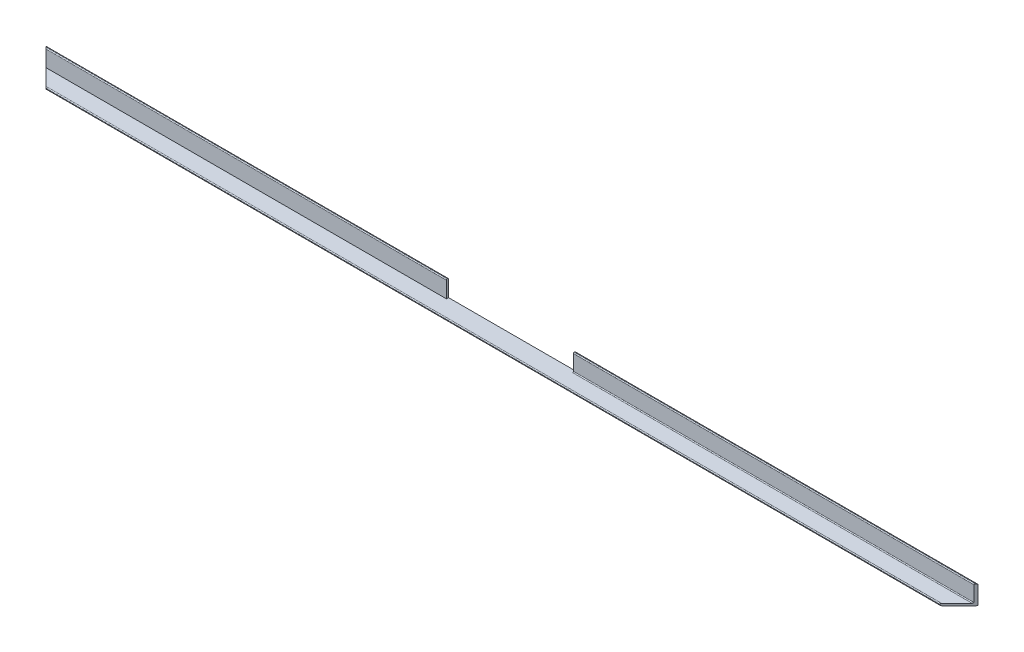
SolidWorks part; units mm, degrees
ref_plane "Front Plane" through (0, 0, 0) normal (0, 0, 1) x (1, 0, 0)
ref_plane "Top Plane" through (0, 0, 0) normal (0, 1, 0) x (1, 0, 0)
ref_plane "Right Plane" through (0, 0, 0) normal (1, 0, 0) x (0, 0, -1)
sketch "Sketch1" plane through (0, 0, 0) normal (0, 1, 0) x (1, 0, 0)
  line L1 (-550, 11.25) -> (550, 11.25)
  line L2 (-550, 11.25) -> (-550, -11.25)
  line L3 (-550, -11.25) -> (550, -11.25)
  line L4 (550, 11.25) -> (550, -11.25)
  line L5 (-550, 11.25) -> (550, -11.25) construction
  line L6 (-550, -11.25) -> (550, 11.25) construction
  point P0 (0, 0)
  dimension "D1" = 1100
  dimension "D2" = 22.5
extrude "Boss-Extrude1" add sketch "Sketch1" along normal blind 2.5
sketch "Sketch2" plane through (0, 2.5, 0) normal (0, 1, 0) x (1, 0, 0)
  line L0 (550, -11.25) -> (550, 11.25) construction
  line L1 (-550, 11.25) -> (550, 11.25)
  line L2 (-550, 11.25) -> (-550, 8.75)
  line L3 (-550, 8.75) -> (550, 8.75)
  line L4 (550, 11.25) -> (550, 8.75)
  dimension "D1" = 2.5
extrude "Boss-Extrude2" add sketch "Sketch2" along normal blind 20
sketch "Sketch3" plane through (0, 0, -8.75) normal (0, 0, 1) x (1, 0, 0)
  line L0 (-550, 22.5) -> (550, 22.5) construction
  line L1 (-75, 22.5) -> (75, 22.5)
  line L2 (-75, 22.5) -> (-75, 2.5)
  line L3 (-75, 2.5) -> (75, 2.5)
  line L4 (75, 22.5) -> (75, 2.5)
  line L5 (-550, 2.5) -> (550, 2.5) construction
  line L6 (-550, 22.5) -> (-550, 2.5) construction
  line L7 (550, 22.5) -> (550, 2.5) construction
  point P10 (-550, 12.5)
  point P13 (550, 12.5)
  dimension "D1" = 150
  dimension "D2" = 475
  dimension "D3" = 475
extrude "Cut-Extrude1" cut sketch "Sketch3" against normal blind 10
sketch "Sketch4" plane through (0, 0, 0) normal (0, -1, 0) x (-1, 0, 0)
  line L0 (-550, 11.25) -> (-527.5, -11.25)
  line L1 (550, -11.25) -> (-550, -11.25) construction
  line L2 (-527.5, -11.25) -> (-550, -11.25)
  line L3 (-550, 11.25) -> (-550, -11.25)
  line L4 (550, -11.25) -> (550, 11.25)
  line L5 (550, 11.25) -> (527.5, -11.25)
  line L7 (527.5, -11.25) -> (550, -11.25)
  dimension "D1" = 45
  dimension "D2" = 45
extrude "Cut-Extrude2" cut sketch "Sketch4" against normal through all
fillet "Fillet1" radius 1 8 edges at (0, 0, 11.25) (0, 2.5, 11.25) (311.25, 22.5, -8.75) (312.5, 22.5, -11.25) (311.25, 2.5, -8.75) (0, 0, -11.25) (-312.5, 22.5, -11.25) (-311.25, 22.5, -8.75)
